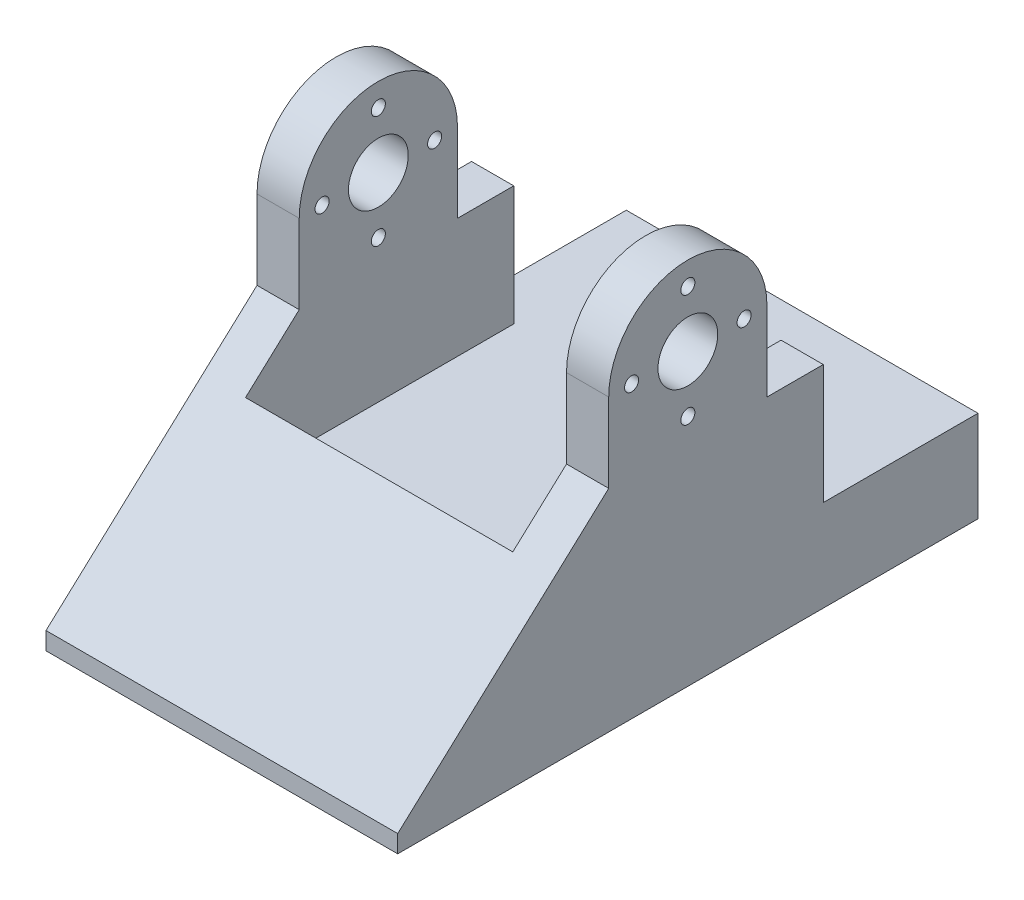
SolidWorks part; units mm, degrees
ref_plane "Front Plane" through (0, 0, 0) normal (0, 0, 1) x (1, 0, 0)
ref_plane "Top Plane" through (0, 0, 0) normal (0, 1, 0) x (1, 0, 0)
ref_plane "Right Plane" through (0, 0, 0) normal (1, 0, 0) x (0, 0, -1)
sketch "Sketch1" plane through (0, 0, 0) normal (0, 0, 1) x (1, 0, 0)
  line L1 (-25, 0) -> (25, 0)
  line L2 (-25, 0) -> (-25, -170)
  line L3 (-25, -170) -> (25, -170)
  line L4 (25, 0) -> (25, -170)
  dimension "D1" = 170
  dimension "D2" = 50
extrude "Boss-Extrude1" add sketch "Sketch1" against normal blind 55
sketch "Sketch2" plane through (0, 0, 0) normal (0, 0, 1) x (1, 0, 0)
  line L0 (25, 0) -> (-25, 0) construction
  line L1 (-17, 0) -> (17, 0)
  line L2 (-17, 0) -> (-17, -27)
  line L3 (-17, -27) -> (17, -27)
  line L4 (17, 0) -> (17, -27)
  line L5 (-25, 0) -> (-25, -170) construction
  dimension "D1" = 8
  dimension "D2" = 34
  dimension "D3" = 27
extrude "Cut-Extrude1" cut sketch "Sketch2" against normal through all
sketch "Sketch3" plane through (25, 0, 0) normal (1, 0, 0) x (0, 0, -1)
  line L0 (0, -170) -> (0, 0) construction
  line L1 (55, -27) -> (0, -27)
  line L2 (55, -27) -> (55, -24)
  line L3 (55, -24) -> (0, -24)
  line L4 (0, -27) -> (0, -24)
  line L5 (55, -170) -> (55, 0) construction
  line L7 (0, 0) -> (10, 0)
  line L8 (0, 0) -> (0, -24)
  line L9 (0, -24) -> (10, -24)
  line L10 (10, 0) -> (10, -24)
  line L11 (55, 0) -> (45, 0)
  line L12 (55, 0) -> (55, -24)
  line L13 (55, -24) -> (45, -24)
  line L14 (45, 0) -> (45, -24)
  circle A0 centre (27.5, -12.75) radius 10.25
  circle A1 centre (27.5, -12.75) radius 4.25
  circle A2 centre (27.5, -12.75) radius 8
  circle A3 centre (27.5, -4.75) radius 1
  circle A4 centre (35.5, -12.75) radius 1
  circle A5 centre (27.5, -20.75) radius 1
  circle A6 centre (19.5, -12.75) radius 1
  point P32 (27.5, -12.75)
  line M7 (0, 0) -> (0, -170)
  line M9 (55, -170) -> (55, 0)
  line M10 (55, 0) -> (0, 0)
  dimension "D2" = 11.25
  dimension "D3" = 27.5
  dimension "D4" = 20.5
  dimension "D7" = 8.5
  dimension "D8" = 16
  dimension "D9" = 4
  dimension "D1" = 3
  dimension "D5" = 10
  dimension "D6" = 10
extrude "Cut-Extrude2" cut sketch "Sketch3" against normal through all contours L14 L3 M10 M9 | L10 L3 M10 M7 | A2 A6 | A2 A6 | A1 | A2 A5 | A2 A5 | A2 A4 | A2 A4 | A2 A3 | A2 A3
sketch "Sketch4" plane through (0, 0, -10) normal (0, 0, 1) x (1, 0, 0)
  line L0 (-25, -24) -> (-17, -24) construction
  line L1 (-17, 0) -> (-19, 0)
  line L2 (-17, 0) -> (-17, -24)
  line L3 (-17, -24) -> (-19, -24)
  line L4 (-19, 0) -> (-19, -24)
  line L5 (0, 0) -> (0, -13.53) construction
  line L6 (19, 0) -> (19, -24)
  line L7 (17, -24) -> (19, -24)
  line L8 (17, 0) -> (17, -24)
  line L9 (17, 0) -> (19, 0)
  dimension "D1" = 2
extrude "Cut-Extrude3" cut sketch "Sketch4" against normal through all
sketch "Sketch5" plane through (25, 0, 0) normal (1, 0, 0) x (0, 0, -1)
  line L1 (10, 0) -> (45, 0)
  line L2 (10, 0) -> (10, -24)
  line L3 (10, -24) -> (45, -24)
  line L4 (45, 0) -> (45, -24)
  line L5 (38.75, -12.75) -> (38.75, -24)
  line L6 (16.25, -12.75) -> (10, -12.75)
  line L7 (16.25, -12.75) -> (16.25, -24)
  line L8 (16.25, -24) -> (10, -24)
  line L9 (10, -12.75) -> (10, -24)
  line L10 (38.75, -12.75) -> (45, -12.75)
  line L11 (38.75, -12.75) -> (38.75, -24)
  line L12 (38.75, -24) -> (45, -24)
  line L13 (45, -12.75) -> (45, -24)
  circle A0 centre (27.5, -12.75) radius 11.25
  line M8 (45, -24) -> (45, 0)
  line M9 (45, 0) -> (10, 0)
  line M10 (10, 0) -> (10, -24)
  dimension "D1" = 22.5
extrude "Cut-Extrude4" cut sketch "Sketch5" against normal through all contours A0 L10 L4 L6 M9 M10 | L7 L6 L2 L3 | L10 L5 L3 M8
sketch "Sketch6" plane through (0, 0, 0) normal (0, 0, 1) x (1, 0, 0)
  line L1 (-19, -24) -> (19, -24)
  line L2 (-19, -24) -> (-19, -34)
  line L3 (-19, -34) -> (19, -34)
  line L4 (19, -24) -> (19, -34)
  dimension "D1" = 10
extrude "Cut-Extrude5" cut sketch "Sketch6" against normal through all
sketch "Sketch8" plane through (25, 0, 0) normal (1, 0, 0) x (0, 0, -1)
  line L0 (55, -170) -> (55, -24) construction
  line L1 (0, -170) -> (0, -24) construction
  line L2 (41.75, -132.5) -> (13.25, -132.5)
  line L3 (27.5, -132.5) -> (27.5, -179)
  line L4 (41.75, -179) -> (13.25, -179)
  line L5 (13.25, -132.5) -> (13.25, -179)
  line L7 (41.75, -132.5) -> (41.75, -179)
  line L11 (27.5, -167.75) -> (55, -167.75)
  line L12 (27.5, -167.75) -> (27.5, -170)
  line L13 (27.5, -170) -> (55, -170)
  line L14 (55, -167.75) -> (55, -170)
  line L16 (27.5, -167.75) -> (0, -167.75)
  line L17 (27.5, -167.75) -> (27.5, -170)
  line L18 (27.5, -170) -> (0, -170)
  line L19 (0, -167.75) -> (0, -170)
  circle A0 centre (27.5, -167.75) radius 10.25
  circle A1 centre (27.5, -12.75) radius 10.25
  line M4 (0, -24) -> (0, -170)
  line M5 (0, -170) -> (55, -170)
  line M6 (55, -170) -> (55, -24)
  dimension "D1" = 27.5
  dimension "D2" = 20.5
  dimension "D3" = 155
  dimension "D4" = 14.25
  dimension "D5" = 11.25
  dimension "D6" = 46.5
  dimension "D7" = 13.25
extrude "Cut-Extrude7" cut sketch "Sketch8" against normal through all contours A0 L3 L2 L5 L16 | A0 L11 L7 L2 L3 | L11 L7 M5 M6 | L5 L16 M4 M5 | A0 L16 L5 M5 | A0 L13 L7 L11 | L3 A0 L16 | L11 A0 L3 | L16 A0 L18 L3 | A0 L11 L3 M5
sketch "Sketch9" plane through (0, 0, 0) normal (0, 0, 1) x (1, 0, 0)
  line L0 (-25, -167.75) -> (25, -167.75) construction
  line L1 (17, -167.75) -> (-17, -167.75)
  line L2 (17, -167.75) -> (17, -132.5)
  line L3 (17, -132.5) -> (-17, -132.5)
  line L4 (-17, -167.75) -> (-17, -132.5)
  line L5 (-25, -132.5) -> (25, -132.5) construction
  line L7 (-25, -24) -> (-25, -167.75) construction
  line L9 (25, -167.75) -> (25, -24) construction
  dimension "D1" = 8
  dimension "D2" = 8
extrude "Cut-Extrude8" cut sketch "Sketch9" against normal through all
sketch "Sketch11" plane through (25, 0, 0) normal (1, 0, 0) x (0, 0, -1)
  line L0 (27.5, -157.5) -> (27.5, -147.5)
  line L2 (27.5, -147.5) -> (55, -147.5)
  line L3 (27.5, -147.5) -> (27.5, -167.75)
  line L4 (27.5, -167.75) -> (55, -167.75)
  line L5 (55, -147.5) -> (55, -167.75)
  line L6 (27.5, -147.5) -> (0, -147.5)
  line L7 (27.5, -147.5) -> (27.5, -167.75)
  line L8 (27.5, -167.75) -> (0, -167.75)
  line L9 (0, -147.5) -> (0, -167.75)
  circle A0 centre (27.5, -167.75) radius 10.25
  arc A1 (38.75, -12.75) -> (16.25, -12.75) centre (27.5, -12.75) ccw construction
  line M1 (0, -167.75) -> (13.25, -167.75)
  line M2 (13.25, -167.75) -> (13.25, -132.5)
  line M4 (41.75, -132.5) -> (41.75, -167.75)
  line M5 (41.75, -167.75) -> (55, -167.75)
  line M6 (55, -167.75) -> (55, -24)
  line M12 (0, -24) -> (0, -167.75)
  dimension "D1" = 155
  dimension "D2" = 20.5
  dimension "D3" = 10
extrude "Cut-Extrude9" cut sketch "Sketch11" against normal through all contours A0 L0 L6 L8 M2 | A0 L4 L2 L0 M4 | L2 M4 M5 M6 | L6 M2 M12 M1
sketch "Sketch12" plane through (25, 0, 0) normal (1, 0, 0) x (0, 0, -1)
  line L1 (13.25, -132.5) -> (41.75, -132.5)
  line L2 (13.25, -132.5) -> (13.25, -147.5)
  line L3 (13.25, -147.5) -> (41.75, -147.5)
  line L4 (41.75, -132.5) -> (41.75, -147.5)
extrude "Boss-Extrude2" add sketch "Sketch12" against normal blind 8
ref_plane "Plane1" through (0, 0, 0) normal (1, 0, 0) x (0, 0, -1)
mirror "Mirror1" about plane through (0, 0, 0) normal (1, 0, 0) of "Boss-Extrude2"
sketch "Sketch14" plane through (0, 0, 0) normal (0, 0, 1) x (1, 0, 0)
  line L0 (17, -148.55) -> (17, -158.75) construction
  line L1 (-17, -132.5) -> (17, -132.5)
  line L2 (-17, -132.5) -> (-17, -147.5)
  line L3 (-17, -147.5) -> (17, -147.5)
  line L4 (17, -132.5) -> (17, -147.5)
  line L5 (-17, -147.5) -> (17, -147.5)
  line L6 (-17, -147.5) -> (-17, -157.75)
  line L7 (-17, -157.75) -> (17, -157.75)
  line L8 (17, -147.5) -> (17, -157.75)
  line M11 (-17, -147.5) -> (-17, -132.5)
  line M12 (-17, -132.5) -> (17, -132.5)
  line M13 (17, -132.5) -> (17, -147.5)
  dimension "D1" = 10.25
extrude "Boss-Extrude3" add sketch "Sketch14" against normal blind 13.25 contours L3 M11 M13 M12 | L8 L3 L6 L7
ref_plane "Plane2" through (0, 0, -27.5) normal (0, 0, 1) x (1, 0, 0)
mirror "Mirror2" about plane through (0, 0, -27.5) normal (0, 0, 1) of "Boss-Extrude3"
sketch "Sketch16" plane through (25, 0, 0) normal (1, 0, 0) x (0, 0, -1)
  line L0 (41.75, -132.5) -> (13.25, -132.5) construction
  line L1 (13.25, -132.5) -> (13.25, -147.5) construction
  circle A1 centre (16.5, -135.75) radius 2.5
  circle A2 centre (16.5, -135.75) radius 4.5
  circle A3 centre (38.5, -135.75) radius 4.5
  dimension "D1" = 3.25
  dimension "D2" = 3.25
  dimension "D3" = 2
extrude "Cut-Extrude13" cut sketch "Sketch16" against normal blind 8 contours A1 | A2 A1 | A3
mirror "Mirror3" about plane through (0, 0, 0) normal (1, 0, 0) of "Cut-Extrude13"
sketch "Sketch17" plane through (25, 0, 0) normal (1, 0, 0) x (0, 0, -1)
  line L0 (55, -147.5) -> (55, -24) construction
  line L1 (27.5, -1.5) -> (55, -1.5)
  line L2 (27.5, -1.5) -> (27.5, -51.5)
  line L3 (27.5, -51.5) -> (55, -51.5)
  line L4 (55, -1.5) -> (55, -51.5)
  line L8 (55, -51.5) -> (0, -51.5)
  line L9 (55, -51.5) -> (55, -157.75)
  line L10 (55, -157.75) -> (0, -157.75)
  line L11 (0, -51.5) -> (0, -157.75)
  arc A0 (38.75, -12.75) -> (16.25, -12.75) centre (27.5, -12.75) ccw construction
  circle M2 centre (16.5, -135.75) radius 4.5
  circle M3 centre (38.5, -135.75) radius 4.5
  line M4 (0, -147.5) -> (55, -147.5)
  line M5 (55, -147.5) -> (55, -24)
  line M11 (0, -24) -> (0, -147.5)
  dimension "D1" = 50
extrude "Cut-Extrude15" cut sketch "Sketch17" against normal through all contours L3 L8 M11 M4 M5 M2 M3 | L11 L10 L9 M4 | M3 | M2
sketch "Sketch18" plane through (25, 0, 0) normal (1, 0, 0) x (0, 0, -1)
  line L1 (38.75, -24) -> (-71.25, -24)
  line L2 (38.75, -24) -> (38.75, -51.5)
  line L3 (38.75, -51.5) -> (-71.25, -51.5)
  line L4 (-71.25, -24) -> (-71.25, -51.5)
  line L6 (38.75, -24) -> (68.75, -24)
  line L7 (38.75, -24) -> (38.75, -51.5)
  line L8 (38.75, -51.5) -> (68.75, -51.5)
  line L9 (68.75, -24) -> (68.75, -51.5)
  line M8 (0, -24) -> (0, -51.5)
  line M9 (0, -51.5) -> (55, -51.5)
  line M10 (55, -51.5) -> (55, -24)
  line M11 (55, -24) -> (38.75, -24)
  line M15 (16.25, -24) -> (0, -24)
  dimension "D1" = 110
  dimension "D2" = 30
extrude "Boss-Extrude4" add sketch "Sketch18" against normal blind 50 contours L1 L4 L3 M8 | L9 L6 L8 M10 | L2 L1 M15 M8 M9 | L2 M11 M9 M10
sketch "Sketch19" plane through (0, 0, 71.25) normal (0, 0, 1) x (1, 0, 0)
  line L1 (-19, -24) -> (19, -24)
  line L2 (-19, -24) -> (-19, -31)
  line L3 (-19, -31) -> (19, -31)
  line L4 (19, -24) -> (19, -31)
  dimension "D1" = 7
extrude "Cut-Extrude16" cut sketch "Sketch19" against normal through all
sketch "Sketch20" plane through (25, 0, 0) normal (1, 0, 0) x (0, 0, -1)
  line L1 (-71.25, -24) -> (68.75, -24)
  line L2 (-71.25, -24) -> (-71.25, -51.5)
  line L3 (-71.25, -51.5) -> (68.75, -51.5)
  line L4 (68.75, -24) -> (68.75, -51.5)
  line L5 (16.25, -24) -> (-13.75, -24)
  line L6 (16.25, -24) -> (16.25, -51.5)
  line L7 (16.25, -51.5) -> (-13.75, -51.5)
  line L8 (-13.75, -24) -> (-13.75, -51.5)
  line L10 (-13.75, -51.5) -> (-71.25, -51.5)
  line L11 (-13.75, -51.5) -> (-13.75, -24)
  line L12 (-13.75, -24) -> (-71.25, -24)
  line L13 (-71.25, -51.5) -> (-71.25, -24)
  line M8 (-71.25, -24) -> (-71.25, -51.5)
  line M9 (-71.25, -51.5) -> (68.75, -51.5)
  dimension "D1" = 30
extrude "Cut-Extrude17" cut sketch "Sketch20" against normal through all contours L8 L1 M8 M9
sketch "Sketch21" plane through (25, 0, 0) normal (1, 0, 0) x (0, 0, -1)
  line L0 (16.25, -24) -> (-13.75, -51.5)
  line L1 (16.25, -24) -> (-13.75, -24)
  line L2 (16.25, -24) -> (16.25, -51.5)
  line L3 (16.25, -51.5) -> (-13.75, -51.5)
  line L4 (-13.75, -24) -> (-13.75, -51.5)
  line M6 (16.25, -24) -> (-13.75, -24)
  line M7 (-13.75, -24) -> (-13.75, -51.5)
extrude "Cut-Extrude18" cut sketch "Sketch21" against normal through all contours L0 M6 M7
sketch "Sketch22" plane through (25, 0, 0) normal (1, 0, 0) x (0, 0, -1)
  line L3 (68.75, -51.5) -> (-13.75, -51.5)
  line L4 (68.75, -51.5) -> (68.75, -54)
  line L5 (68.75, -54) -> (-13.75, -54)
  line L6 (-13.75, -51.5) -> (-13.75, -54)
  dimension "D1" = 2.5
extrude "Boss-Extrude5" add sketch "Sketch22" against normal blind 50
sketch "Sketch24" plane through (25, 0, 0) normal (1, 0, 0) x (0, 0, -1)
  line L1 (68.75, -24) -> (46.75, -24)
  line L2 (68.75, -24) -> (68.75, -41)
  line L3 (68.75, -41) -> (46.75, -41)
  line L4 (46.75, -24) -> (46.75, -41)
  dimension "D1" = 17
  dimension "D2" = 22
extrude "Cut-Extrude19" cut sketch "Sketch24" against normal through all
sketch "Sketch25" plane through (0, -31, 0) normal (0, 1, 0) x (1, 0, 0)
  line L1 (-19, 46.75) -> (19, 46.75)
  line L2 (-19, 46.75) -> (-19, 8.6136)
  line L3 (-19, 8.6136) -> (19, 8.6136)
  line L4 (19, 46.75) -> (19, 8.6136)
extrude "Cut-Extrude20" cut sketch "Sketch25" against normal blind 10
